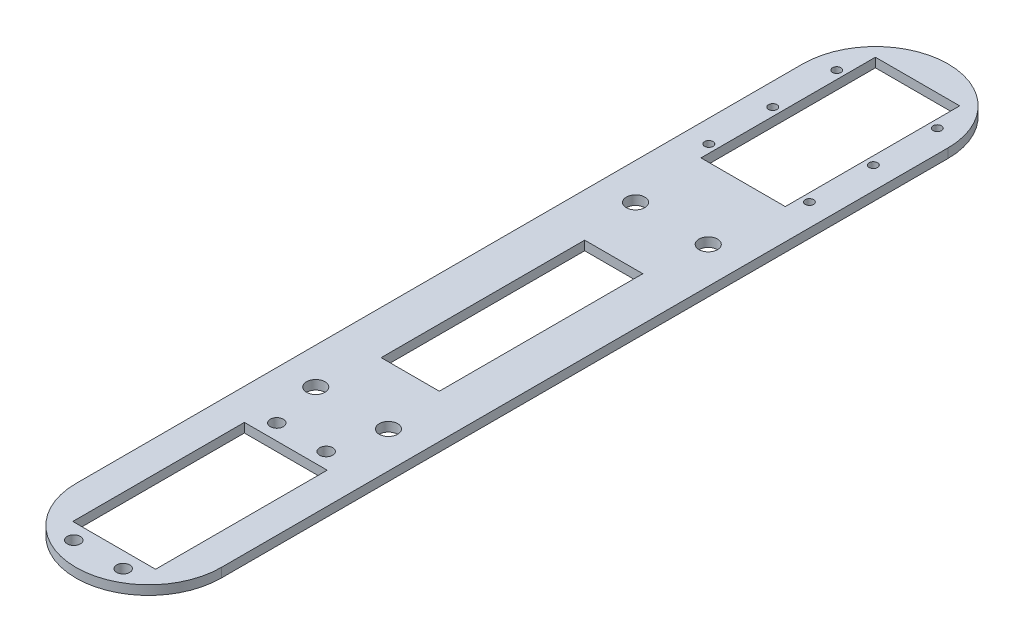
SolidWorks part; units mm, degrees
ref_plane "Front" through (0, 0, 0) normal (0, 0, 1) x (1, 0, 0)
ref_plane "Top" through (0, 0, 0) normal (0, 1, 0) x (1, 0, 0)
ref_plane "Right" through (0, 0, 0) normal (1, 0, 0) x (0, 0, -1)
sketch "Sketch2" plane through (0, 0, 0) normal (0, 1, 0) x (1, 0, 0)
  line L1 (0, 0) -> (50, 0)
  line L2 (0, 0) -> (0, -300)
  line L3 (0, -300) -> (50, -300)
  line L4 (50, 0) -> (50, -300)
  dimension "D1" = 300
  dimension "D2" = 50
extrude "Boss-Extrude1" add sketch "Sketch2" along normal blind 3.175
sketch "Sketch3" plane through (0, 3.175, 0) normal (0, 1, 0) x (1, 0, 0)
  line L0 (25, 0) -> (25, -300) construction
  line L1 (50, 0) -> (0, 0) construction
  line L2 (0, -300) -> (50, -300) construction
  line L3 (0, -150) -> (50, -150) construction
  line L4 (0, 0) -> (0, -300) construction
  line L5 (50, -300) -> (50, 0) construction
  line L6 (39.24, -257.325) -> (10.76, -257.325) construction
  line L7 (10.5, -10.5) -> (39.5, -10.5)
  line L8 (10.5, -10.5) -> (10.5, -70.5)
  line L9 (10.5, -70.5) -> (39.5, -70.5)
  line L10 (39.5, -10.5) -> (39.5, -70.5)
  line L11 (10.76, -227.81) -> (39.24, -227.81)
  line L12 (10.76, -227.81) -> (10.76, -286.84)
  line L13 (10.76, -286.84) -> (39.24, -286.84)
  line L14 (39.24, -227.81) -> (39.24, -286.84)
  circle A0 centre (7.7, -21) radius 1.025
  circle A1 centre (7.7, -43) radius 1.025
  circle A2 centre (7.7, -65) radius 1.025
  circle A3 centre (42.3, -65) radius 1.025
  circle A4 centre (42.3, -43) radius 1.025
  circle A5 centre (42.3, -21) radius 1.025
  circle A6 centre (16.5, -292.24) radius 2.25
  circle A7 centre (33.5, -292.24) radius 2.25
  circle A8 centre (16.5, -222.41) radius 2.25
  circle A9 centre (33.5, -222.41) radius 2.25
  dimension "D4" = 2.05
  dimension "D5" = 22
  dimension "D6" = 22
  dimension "D7" = 5.5
  dimension "D8" = 2.8
  dimension "D12" = 4.5
  dimension "D13" = 5.4
  dimension "D14" = 8.5
  dimension "D1" = 60
  dimension "D2" = 10.5
  dimension "D3" = 29
  dimension "D9" = 28.48
  dimension "D10" = 59.03
  dimension "D11" = 13.16
extrude "Cut-Extrude1" cut sketch "Sketch3" against normal blind 6.35
sketch "Sketch4" plane through (0, 3.175, 0) normal (0, 1, 0) x (1, 0, 0)
  line L0 (0, -25) -> (0, 0)
  line L1 (0, 0) -> (50, 0)
  line L2 (50, 0) -> (50, -25)
  line L3 (0, -275) -> (0, -300)
  line L4 (0, -300) -> (50, -300)
  line L5 (50, -300) -> (50, -275)
  circle A0 centre (25, -25) radius 25
  circle A1 centre (25, -275) radius 25
  line M19 (0, 0) -> (0, -300)
  line M20 (0, -300) -> (50, -300)
  line M21 (50, -300) -> (50, 0)
  line M22 (50, 0) -> (0, 0)
extrude "Cut-Extrude2" cut sketch "Sketch4" against normal blind 6.35 contours A0 L1 M19 | A0 M21 M22 | A1 M19 M20 | A1 L4 M21
sketch "Sketch5" plane through (0, 0, 0) normal (0, -1, 0) x (1, 0, 0)
  line L0 (25, 300) -> (25, 0) construction
  line L1 (0, 150) -> (50, 150) construction
  line L2 (0, 25) -> (0, 275) construction
  line L3 (50, 275) -> (50, 25) construction
  line L5 (15, 185) -> (35, 185)
  line L6 (15, 185) -> (15, 115)
  line L7 (15, 115) -> (35, 115)
  line L8 (35, 185) -> (35, 115)
  arc A0 (50, 275) -> (0, 275) centre (25, 275) ccw construction
  arc A1 (0, 25) -> (50, 25) centre (25, 25) ccw construction
  circle A2 centre (12.5, 205) radius 3.175
  circle A3 centre (12.5, 95) radius 3.175
  circle A4 centre (37.5, 95) radius 3.175
  circle A5 centre (37.5, 205) radius 3.175
  dimension "D3" = 6.35
  dimension "D4" = 55
  dimension "D5" = 12.5
  dimension "D1" = 20
  dimension "D2" = 70
extrude "Cut-Extrude3" cut sketch "Sketch5" against normal blind 6.35
hole_wizard "M2.5 Clearance Hole1" positions "Sketch7" profile "Sketch6" hole size "M2.5" standard "ANSI Metric" end condition through all
sketch "Sketch7" plane through (0, 0, 0) normal (0, -1, 0) x (-1, 0, 0)
  point P0 (-7.7, -65)
  point P3 (-42.3, -65)
  point P6 (-7.7, -43)
  point P9 (-42.3, -43)
  point P12 (-42.3, -21)
  point P15 (-7.7, -21)
sketch "Sketch6" plane through (7.7, 0, 65) normal (1, 0, 0) x (0, 0, -1)
  line L0 (0, 0) -> (0, 3.175)
  line L1 (0, 3.175) -> (1.45, 3.175)
  line L2 (1.45, 3.175) -> (1.45, 0)
  line L5 (1.45, 0) -> (0, 0)
  line L11 (0, -6.35) -> (0, 107.95) construction
  dimension "Thru Hole Dia." = 2.9
  dimension "Thru Hole Depth" = 3.175
